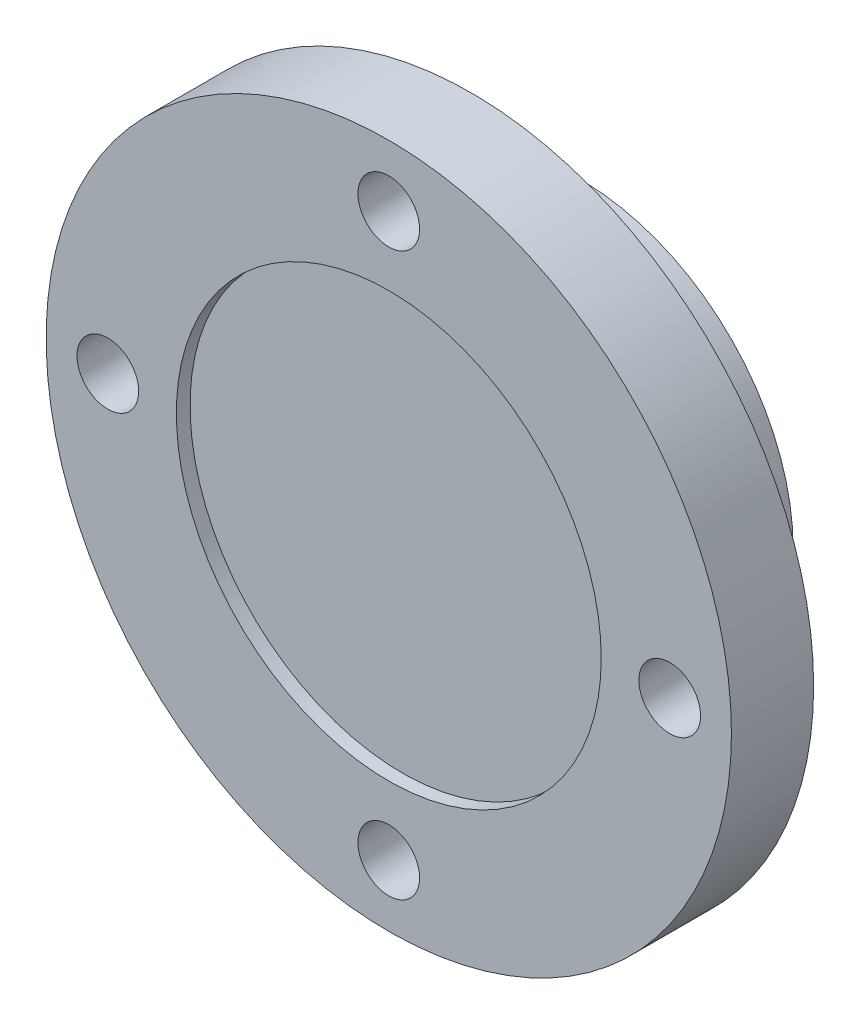
SolidWorks part; units mm, degrees
ref_plane "前视基准面" through (0, 0, 0) normal (0, 0, 1) x (1, 0, 0)
ref_plane "上视基准面" through (0, 0, 0) normal (0, 1, 0) x (1, 0, 0)
ref_plane "右视基准面" through (0, 0, 0) normal (1, 0, 0) x (0, 0, -1)
other "Configuration Table"
sketch "草图1" plane through (0, 0, 0) normal (0, 1, 0) x (1, 0, 0)
  line L0 (-20.4689, 10) -> (20.4689, 10)
  line L1 (-31, 0) -> (31, 0)
  line L2 (0, 0) -> (0, 10) construction
  line L4 (50, -2) -> (50, 10)
  line L7 (50, -2) -> (31, -2)
  line L8 (31, 0) -> (31, -2)
  line L9 (24.438, 13.5039) -> (26, 26)
  line L10 (26, 26) -> (31, 26)
  line L11 (31, 26) -> (31, 10)
  line L12 (31, 10) -> (50, 10)
  line L13 (-31, 10) -> (-50, 10)
  line L14 (-31, 26) -> (-31, 10)
  line L15 (-26, 26) -> (-31, 26)
  line L16 (-24.438, 13.5039) -> (-26, 26)
  line L17 (-31, 0) -> (-31, -2)
  line L18 (-50, -2) -> (-31, -2)
  line L20 (-50, -2) -> (-50, 10)
  line L21 (0, 0) -> (0, 10)
  arc A2 (-24.438, 13.5039) -> (-20.4689, 10) centre (-20.4689, 14) ccw
  arc A3 (20.4689, 10) -> (24.438, 13.5039) centre (20.4689, 14) ccw
  point P2 (0, 0)
  point P13 (-24, 10)
  point P18 (24, 10)
  dimension "D1" = 4
  dimension "D2" = 16
  dimension "D3" = 28
  dimension "D4" = 2
  dimension "D5" = 62
  dimension "D6" = 62
  dimension "D7" = 48
  dimension "D8" = 52
  dimension "D9" = 100
revolve "旋转4" add sketch "草图1" angle 360 about L2
sketch "草图2" plane through (0, 0, -10) normal (0, 0, -1) x (-1, 0, 0)
  circle A0 centre (41, 0) radius 4.5
  circle A1 centre (0, -41) radius 4.5
  circle A2 centre (-41, 0) radius 4.5
  circle A3 centre (0, 41) radius 4.5
  point P2 (-43.9148, 10.9577)
  point P12 (0, 0)
  dimension "D1" = 9
  dimension "D2" = 41
  dimension "D3" = 4
extrude "切除-拉伸1" cut sketch "草图2" against normal through all
